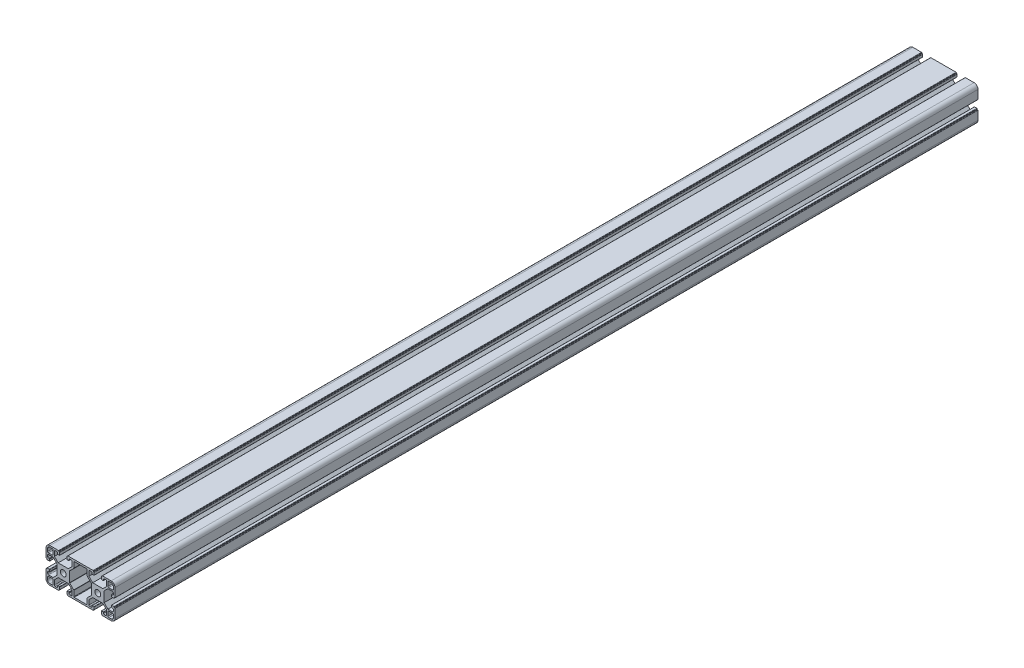
SolidWorks part; units mm, degrees
ref_plane "Front Plane" through (0, 0, 0) normal (0, 0, 1) x (1, 0, 0)
ref_plane "Top Plane" through (0, 0, 0) normal (0, 1, 0) x (1, 0, 0)
ref_plane "Right Plane" through (0, 0, 0) normal (1, 0, 0) x (0, 0, -1)
sketch "Model" plane through (0, 0, 0) normal (0, 0, 1) x (1, 0, 0)
  line L0 (3124.8642, 1448.2024) -> (3124.8642, 1456.7024) construction
  line L1 (3120.6142, 1452.4524) -> (3129.1142, 1452.4524) construction
  line L2 (3180.3642, 1470.6524) -> (3177.6142, 1470.6524)
  line L3 (3183.0642, 1465.2024) -> (3183.0642, 1467.9524)
  line L4 (3176.6142, 1469.6524) -> (3176.6142, 1465.2024)
  line L5 (3177.6142, 1464.2024) -> (3182.0642, 1464.2024)
  line L6 (3183.0642, 1436.9524) -> (3183.0642, 1439.7024)
  line L7 (3177.6142, 1434.2524) -> (3180.3642, 1434.2524)
  line L8 (3182.0642, 1440.7024) -> (3177.6142, 1440.7024)
  line L9 (3176.6142, 1439.7024) -> (3176.6142, 1435.2524)
  line L10 (3106.6642, 1465.2024) -> (3106.6642, 1467.9524)
  line L11 (3109.3642, 1470.6524) -> (3112.1142, 1470.6524)
  line L12 (3112.1142, 1464.2024) -> (3107.6642, 1464.2024)
  line L13 (3113.1142, 1469.6524) -> (3113.1142, 1465.2024)
  line L14 (3152.6142, 1434.9524) -> (3152.6142, 1441.3388)
  line L15 (3137.1142, 1441.3388) -> (3137.1142, 1434.9524)
  line L16 (3152.7606, 1441.6923) -> (3157.3177, 1446.2494)
  line L17 (3132.4106, 1446.2494) -> (3136.9677, 1441.6923)
  line L18 (3157.4642, 1446.603) -> (3157.4642, 1458.3018)
  line L19 (3132.2642, 1458.3018) -> (3132.2642, 1446.603)
  line L20 (3157.3177, 1458.6553) -> (3152.7606, 1463.2124)
  line L21 (3136.9677, 1463.2124) -> (3132.4106, 1458.6553)
  line L22 (3152.6142, 1463.566) -> (3152.6142, 1469.9524)
  line L23 (3137.1142, 1469.9524) -> (3137.1142, 1463.566)
  line L24 (3112.1142, 1434.2524) -> (3109.3642, 1434.2524)
  line L25 (3106.6642, 1436.9524) -> (3106.6642, 1439.7024)
  line L26 (3113.1142, 1439.7024) -> (3113.1142, 1435.2524)
  line L27 (3107.6642, 1440.7024) -> (3112.1142, 1440.7024)
  line L28 (3107.8642, 1445.8524) -> (3108.8642, 1445.8524)
  line L29 (3106.8642, 1443.2024) -> (3106.8642, 1444.8524)
  line L30 (3109.1642, 1446.1524) -> (3109.1642, 1448.0524)
  line L31 (3113.1293, 1442.2024) -> (3107.8642, 1442.2024)
  line L32 (3117.4642, 1446.5373) -> (3113.1293, 1442.2024)
  line L33 (3108.8642, 1448.3524) -> (3106.1642, 1448.3524)
  line L34 (3117.4642, 1458.3674) -> (3117.4642, 1446.5373)
  line L35 (3113.1293, 1462.7024) -> (3117.4642, 1458.3674)
  line L36 (3105.8642, 1448.0524) -> (3105.8642, 1447.5524)
  line L37 (3107.8642, 1462.7024) -> (3113.1293, 1462.7024)
  line L38 (3105.6642, 1447.3524) -> (3105.1642, 1447.3524)
  line L39 (3106.8642, 1460.0524) -> (3106.8642, 1461.7024)
  line L40 (3104.8642, 1447.0524) -> (3104.8642, 1436.9524)
  line L41 (3108.8642, 1459.0524) -> (3107.8642, 1459.0524)
  line L42 (3109.3642, 1432.4524) -> (3119.4642, 1432.4524)
  line L43 (3109.1642, 1456.8524) -> (3109.1642, 1458.7524)
  line L44 (3119.7642, 1432.7524) -> (3119.7642, 1433.2524)
  line L45 (3106.1642, 1456.5524) -> (3108.8642, 1456.5524)
  line L46 (3119.9642, 1433.4524) -> (3120.4642, 1433.4524)
  line L47 (3105.8642, 1457.3524) -> (3105.8642, 1456.8524)
  line L48 (3120.7642, 1433.7524) -> (3120.7642, 1436.4524)
  line L49 (3105.1642, 1457.5524) -> (3105.6642, 1457.5524)
  line L50 (3120.4642, 1436.7524) -> (3118.5642, 1436.7524)
  line L51 (3104.8642, 1467.9524) -> (3104.8642, 1457.8524)
  line L52 (3118.2642, 1436.4524) -> (3118.2642, 1435.4524)
  line L53 (3119.4642, 1472.4524) -> (3109.3642, 1472.4524)
  line L54 (3117.2642, 1434.4524) -> (3115.6142, 1434.4524)
  line L55 (3119.7642, 1471.6524) -> (3119.7642, 1472.1524)
  line L56 (3114.6142, 1435.4524) -> (3114.6142, 1440.7174)
  line L57 (3120.4642, 1471.4524) -> (3119.9642, 1471.4524)
  line L58 (3114.6142, 1440.7174) -> (3118.9491, 1445.0524)
  line L59 (3118.9491, 1445.0524) -> (3130.7793, 1445.0524)
  line L60 (3120.7642, 1468.4524) -> (3120.7642, 1471.1524)
  line L61 (3130.7793, 1445.0524) -> (3135.1142, 1440.7174)
  line L62 (3135.1142, 1440.7174) -> (3135.1142, 1435.4524)
  line L63 (3118.5642, 1468.1524) -> (3120.4642, 1468.1524)
  line L64 (3134.1142, 1434.4524) -> (3132.4642, 1434.4524)
  line L65 (3118.2642, 1469.4524) -> (3118.2642, 1468.4524)
  line L66 (3131.4642, 1435.4524) -> (3131.4642, 1436.4524)
  line L67 (3115.6142, 1470.4524) -> (3117.2642, 1470.4524)
  line L68 (3131.1642, 1436.7524) -> (3129.2642, 1436.7524)
  line L69 (3114.6142, 1464.1873) -> (3114.6142, 1469.4524)
  line L70 (3118.9491, 1459.8524) -> (3114.6142, 1464.1873)
  line L71 (3128.9642, 1436.4524) -> (3128.9642, 1433.7524)
  line L72 (3130.7793, 1459.8524) -> (3118.9491, 1459.8524)
  line L73 (3135.1142, 1464.1873) -> (3130.7793, 1459.8524)
  line L74 (3129.2642, 1433.4524) -> (3129.7642, 1433.4524)
  line L75 (3135.1142, 1469.4524) -> (3135.1142, 1464.1873)
  line L76 (3129.9642, 1433.2524) -> (3129.9642, 1432.7524)
  line L77 (3132.4642, 1470.4524) -> (3134.1142, 1470.4524)
  line L78 (3131.4642, 1468.4524) -> (3131.4642, 1469.4524)
  line L79 (3129.2642, 1468.1524) -> (3131.1642, 1468.1524)
  line L80 (3159.7642, 1432.7524) -> (3159.7642, 1433.2524)
  line L81 (3128.9642, 1471.1524) -> (3128.9642, 1468.4524)
  line L82 (3159.9642, 1433.4524) -> (3160.4642, 1433.4524)
  line L83 (3129.7642, 1471.4524) -> (3129.2642, 1471.4524)
  line L84 (3160.7642, 1433.7524) -> (3160.7642, 1436.4524)
  line L85 (3129.9642, 1472.1524) -> (3129.9642, 1471.6524)
  line L86 (3160.4642, 1436.7524) -> (3158.5642, 1436.7524)
  line L87 (3158.2642, 1436.4524) -> (3158.2642, 1435.4524)
  line L88 (3157.2642, 1434.4524) -> (3155.6142, 1434.4524)
  line L89 (3159.7642, 1471.6524) -> (3159.7642, 1472.1524)
  line L90 (3154.6142, 1435.4524) -> (3154.6142, 1440.7174)
  line L91 (3160.4642, 1471.4524) -> (3159.9642, 1471.4524)
  line L92 (3154.6142, 1440.7174) -> (3158.9491, 1445.0524)
  line L93 (3158.9491, 1445.0524) -> (3170.7793, 1445.0524)
  line L94 (3160.7642, 1468.4524) -> (3160.7642, 1471.1524)
  line L95 (3170.7793, 1445.0524) -> (3175.1142, 1440.7174)
  line L96 (3175.1142, 1440.7174) -> (3175.1142, 1435.4524)
  line L97 (3158.5642, 1468.1524) -> (3160.4642, 1468.1524)
  line L98 (3174.1142, 1434.4524) -> (3172.4642, 1434.4524)
  line L99 (3158.2642, 1469.4524) -> (3158.2642, 1468.4524)
  line L100 (3171.4642, 1435.4524) -> (3171.4642, 1436.4524)
  line L101 (3155.6142, 1470.4524) -> (3157.2642, 1470.4524)
  line L102 (3171.1642, 1436.7524) -> (3169.2642, 1436.7524)
  line L103 (3154.6142, 1464.1873) -> (3154.6142, 1469.4524)
  line L104 (3158.9491, 1459.8524) -> (3154.6142, 1464.1873)
  line L105 (3168.9642, 1436.4524) -> (3168.9642, 1433.7524)
  line L106 (3170.7793, 1459.8524) -> (3158.9491, 1459.8524)
  line L107 (3175.1142, 1464.1873) -> (3170.7793, 1459.8524)
  line L108 (3169.2642, 1433.4524) -> (3169.7642, 1433.4524)
  line L109 (3175.1142, 1469.4524) -> (3175.1142, 1464.1873)
  line L110 (3169.9642, 1433.2524) -> (3169.9642, 1432.7524)
  line L111 (3172.4642, 1470.4524) -> (3174.1142, 1470.4524)
  line L112 (3170.2642, 1432.4524) -> (3180.3642, 1432.4524)
  line L113 (3171.4642, 1468.4524) -> (3171.4642, 1469.4524)
  line L114 (3184.8642, 1436.9524) -> (3184.8642, 1447.0524)
  line L115 (3169.2642, 1468.1524) -> (3171.1642, 1468.1524)
  line L116 (3184.5642, 1447.3524) -> (3184.0642, 1447.3524)
  line L117 (3168.9642, 1471.1524) -> (3168.9642, 1468.4524)
  line L118 (3183.8642, 1447.5524) -> (3183.8642, 1448.0524)
  line L119 (3169.7642, 1471.4524) -> (3169.2642, 1471.4524)
  line L120 (3183.5642, 1448.3524) -> (3180.8642, 1448.3524)
  line L121 (3169.9642, 1472.1524) -> (3169.9642, 1471.6524)
  line L122 (3180.5642, 1448.0524) -> (3180.5642, 1446.1524)
  line L123 (3180.3642, 1472.4524) -> (3170.2642, 1472.4524)
  line L124 (3180.8642, 1445.8524) -> (3181.8642, 1445.8524)
  line L125 (3184.8642, 1457.8524) -> (3184.8642, 1467.9524)
  line L126 (3182.8642, 1444.8524) -> (3182.8642, 1443.2024)
  line L127 (3184.0642, 1457.5524) -> (3184.5642, 1457.5524)
  line L128 (3181.8642, 1442.2024) -> (3176.5991, 1442.2024)
  line L129 (3183.8642, 1456.8524) -> (3183.8642, 1457.3524)
  line L130 (3176.5991, 1442.2024) -> (3172.2642, 1446.5373)
  line L131 (3172.2642, 1446.5373) -> (3172.2642, 1458.3674)
  line L132 (3180.8642, 1456.5524) -> (3183.5642, 1456.5524)
  line L133 (3172.2642, 1458.3674) -> (3176.5991, 1462.7024)
  line L134 (3176.5991, 1462.7024) -> (3181.8642, 1462.7024)
  line L135 (3180.5642, 1458.7524) -> (3180.5642, 1456.8524)
  line L136 (3182.8642, 1461.7024) -> (3182.8642, 1460.0524)
  line L137 (3181.8642, 1459.0524) -> (3180.8642, 1459.0524)
  line L138 (3164.8642, 1448.2024) -> (3164.8642, 1456.7024) construction
  line L139 (3160.6142, 1452.4524) -> (3169.1142, 1452.4524) construction
  line L140 (3130.2642, 1432.4524) -> (3159.4642, 1432.4524)
  line L141 (3152.1142, 1434.4524) -> (3137.6142, 1434.4524)
  line L142 (3130.2642, 1472.4524) -> (3159.4642, 1472.4524)
  line L143 (3152.1142, 1470.4524) -> (3137.6142, 1470.4524)
  circle A0 centre (3164.8642, 1452.4524) radius 3.4
  arc A1 (3183.0642, 1467.9524) -> (3180.3642, 1470.6524) centre (3180.3642, 1467.9524) ccw
  arc A2 (3177.6142, 1470.6524) -> (3176.6142, 1469.6524) centre (3177.6142, 1469.6524) ccw
  arc A3 (3182.0642, 1464.2024) -> (3183.0642, 1465.2024) centre (3182.0642, 1465.2024) ccw
  arc A4 (3176.6142, 1465.2024) -> (3177.6142, 1464.2024) centre (3177.6142, 1465.2024) ccw
  arc A5 (3180.3642, 1434.2524) -> (3183.0642, 1436.9524) centre (3180.3642, 1436.9524) ccw
  arc A6 (3183.0642, 1439.7024) -> (3182.0642, 1440.7024) centre (3182.0642, 1439.7024) ccw
  arc A7 (3176.6142, 1435.2524) -> (3177.6142, 1434.2524) centre (3177.6142, 1435.2524) ccw
  arc A8 (3177.6142, 1440.7024) -> (3176.6142, 1439.7024) centre (3177.6142, 1439.7024) ccw
  circle A9 centre (3124.8642, 1452.4524) radius 3.4
  arc A10 (3109.3642, 1470.6524) -> (3106.6642, 1467.9524) centre (3109.3642, 1467.9524) ccw
  arc A11 (3106.6642, 1465.2024) -> (3107.6642, 1464.2024) centre (3107.6642, 1465.2024) ccw
  arc A12 (3113.1142, 1469.6524) -> (3112.1142, 1470.6524) centre (3112.1142, 1469.6524) ccw
  arc A13 (3112.1142, 1464.2024) -> (3113.1142, 1465.2024) centre (3112.1142, 1465.2024) ccw
  arc A14 (3152.1142, 1434.4524) -> (3152.6142, 1434.9524) centre (3152.1142, 1434.9524) ccw
  arc A15 (3137.1142, 1434.9524) -> (3137.6142, 1434.4524) centre (3137.6142, 1434.9524) ccw
  arc A16 (3152.7606, 1441.6923) -> (3152.6142, 1441.3388) centre (3153.1142, 1441.3388) ccw
  arc A17 (3137.1142, 1441.3388) -> (3136.9677, 1441.6923) centre (3136.6142, 1441.3388) ccw
  arc A18 (3157.3177, 1446.2494) -> (3157.4642, 1446.603) centre (3156.9642, 1446.603) ccw
  arc A19 (3132.2642, 1446.603) -> (3132.4106, 1446.2494) centre (3132.7642, 1446.603) ccw
  arc A20 (3157.4642, 1458.3018) -> (3157.3177, 1458.6553) centre (3156.9642, 1458.3018) ccw
  arc A21 (3132.4106, 1458.6553) -> (3132.2642, 1458.3018) centre (3132.7642, 1458.3018) ccw
  arc A22 (3152.6142, 1463.566) -> (3152.7606, 1463.2124) centre (3153.1142, 1463.566) ccw
  arc A23 (3136.9677, 1463.2124) -> (3137.1142, 1463.566) centre (3136.6142, 1463.566) ccw
  arc A24 (3152.6142, 1469.9524) -> (3152.1142, 1470.4524) centre (3152.1142, 1469.9524) ccw
  arc A25 (3137.6142, 1470.4524) -> (3137.1142, 1469.9524) centre (3137.6142, 1469.9524) ccw
  arc A26 (3106.6642, 1436.9524) -> (3109.3642, 1434.2524) centre (3109.3642, 1436.9524) ccw
  arc A27 (3112.1142, 1434.2524) -> (3113.1142, 1435.2524) centre (3112.1142, 1435.2524) ccw
  arc A28 (3107.6642, 1440.7024) -> (3106.6642, 1439.7024) centre (3107.6642, 1439.7024) ccw
  arc A29 (3113.1142, 1439.7024) -> (3112.1142, 1440.7024) centre (3112.1142, 1439.7024) ccw
  arc A30 (3107.8642, 1445.8524) -> (3106.8642, 1444.8524) centre (3107.8642, 1444.8524) ccw
  arc A31 (3108.8642, 1445.8524) -> (3109.1642, 1446.1524) centre (3108.8642, 1446.1524) ccw
  arc A32 (3106.8642, 1443.2024) -> (3107.8642, 1442.2024) centre (3107.8642, 1443.2024) ccw
  arc A33 (3109.1642, 1448.0524) -> (3108.8642, 1448.3524) centre (3108.8642, 1448.0524) ccw
  arc A34 (3106.1642, 1448.3524) -> (3105.8642, 1448.0524) centre (3106.1642, 1448.0524) ccw
  arc A35 (3105.6642, 1447.3524) -> (3105.8642, 1447.5524) centre (3105.6642, 1447.5524) ccw
  arc A36 (3107.8642, 1462.7024) -> (3106.8642, 1461.7024) centre (3107.8642, 1461.7024) ccw
  arc A37 (3105.1642, 1447.3524) -> (3104.8642, 1447.0524) centre (3105.1642, 1447.0524) ccw
  arc A38 (3106.8642, 1460.0524) -> (3107.8642, 1459.0524) centre (3107.8642, 1460.0524) ccw
  arc A39 (3104.8642, 1436.9524) -> (3109.3642, 1432.4524) centre (3109.3642, 1436.9524) ccw
  arc A40 (3109.1642, 1458.7524) -> (3108.8642, 1459.0524) centre (3108.8642, 1458.7524) ccw
  arc A41 (3119.4642, 1432.4524) -> (3119.7642, 1432.7524) centre (3119.4642, 1432.7524) ccw
  arc A42 (3108.8642, 1456.5524) -> (3109.1642, 1456.8524) centre (3108.8642, 1456.8524) ccw
  arc A43 (3119.9642, 1433.4524) -> (3119.7642, 1433.2524) centre (3119.9642, 1433.2524) ccw
  arc A44 (3105.8642, 1456.8524) -> (3106.1642, 1456.5524) centre (3106.1642, 1456.8524) ccw
  arc A45 (3120.4642, 1433.4524) -> (3120.7642, 1433.7524) centre (3120.4642, 1433.7524) ccw
  arc A46 (3105.8642, 1457.3524) -> (3105.6642, 1457.5524) centre (3105.6642, 1457.3524) ccw
  arc A47 (3120.7642, 1436.4524) -> (3120.4642, 1436.7524) centre (3120.4642, 1436.4524) ccw
  arc A48 (3104.8642, 1457.8524) -> (3105.1642, 1457.5524) centre (3105.1642, 1457.8524) ccw
  arc A49 (3118.5642, 1436.7524) -> (3118.2642, 1436.4524) centre (3118.5642, 1436.4524) ccw
  arc A50 (3109.3642, 1472.4524) -> (3104.8642, 1467.9524) centre (3109.3642, 1467.9524) ccw
  arc A51 (3117.2642, 1434.4524) -> (3118.2642, 1435.4524) centre (3117.2642, 1435.4524) ccw
  arc A52 (3119.7642, 1472.1524) -> (3119.4642, 1472.4524) centre (3119.4642, 1472.1524) ccw
  arc A53 (3114.6142, 1435.4524) -> (3115.6142, 1434.4524) centre (3115.6142, 1435.4524) ccw
  arc A54 (3119.7642, 1471.6524) -> (3119.9642, 1471.4524) centre (3119.9642, 1471.6524) ccw
  arc A55 (3120.7642, 1471.1524) -> (3120.4642, 1471.4524) centre (3120.4642, 1471.1524) ccw
  arc A56 (3120.4642, 1468.1524) -> (3120.7642, 1468.4524) centre (3120.4642, 1468.4524) ccw
  arc A57 (3134.1142, 1434.4524) -> (3135.1142, 1435.4524) centre (3134.1142, 1435.4524) ccw
  arc A58 (3118.2642, 1468.4524) -> (3118.5642, 1468.1524) centre (3118.5642, 1468.4524) ccw
  arc A59 (3131.4642, 1435.4524) -> (3132.4642, 1434.4524) centre (3132.4642, 1435.4524) ccw
  arc A60 (3118.2642, 1469.4524) -> (3117.2642, 1470.4524) centre (3117.2642, 1469.4524) ccw
  arc A61 (3131.4642, 1436.4524) -> (3131.1642, 1436.7524) centre (3131.1642, 1436.4524) ccw
  arc A62 (3115.6142, 1470.4524) -> (3114.6142, 1469.4524) centre (3115.6142, 1469.4524) ccw
  arc A63 (3129.2642, 1436.7524) -> (3128.9642, 1436.4524) centre (3129.2642, 1436.4524) ccw
  arc A64 (3128.9642, 1433.7524) -> (3129.2642, 1433.4524) centre (3129.2642, 1433.7524) ccw
  arc A65 (3129.9642, 1433.2524) -> (3129.7642, 1433.4524) centre (3129.7642, 1433.2524) ccw
  arc A66 (3135.1142, 1469.4524) -> (3134.1142, 1470.4524) centre (3134.1142, 1469.4524) ccw
  arc A67 (3129.9642, 1432.7524) -> (3130.2642, 1432.4524) centre (3130.2642, 1432.7524) ccw
  arc A68 (3132.4642, 1470.4524) -> (3131.4642, 1469.4524) centre (3132.4642, 1469.4524) ccw
  arc A69 (3131.1642, 1468.1524) -> (3131.4642, 1468.4524) centre (3131.1642, 1468.4524) ccw
  arc A70 (3159.4642, 1432.4524) -> (3159.7642, 1432.7524) centre (3159.4642, 1432.7524) ccw
  arc A71 (3128.9642, 1468.4524) -> (3129.2642, 1468.1524) centre (3129.2642, 1468.4524) ccw
  arc A72 (3159.9642, 1433.4524) -> (3159.7642, 1433.2524) centre (3159.9642, 1433.2524) ccw
  arc A73 (3129.2642, 1471.4524) -> (3128.9642, 1471.1524) centre (3129.2642, 1471.1524) ccw
  arc A74 (3160.4642, 1433.4524) -> (3160.7642, 1433.7524) centre (3160.4642, 1433.7524) ccw
  arc A75 (3129.7642, 1471.4524) -> (3129.9642, 1471.6524) centre (3129.7642, 1471.6524) ccw
  arc A76 (3160.7642, 1436.4524) -> (3160.4642, 1436.7524) centre (3160.4642, 1436.4524) ccw
  arc A77 (3130.2642, 1472.4524) -> (3129.9642, 1472.1524) centre (3130.2642, 1472.1524) ccw
  arc A78 (3158.5642, 1436.7524) -> (3158.2642, 1436.4524) centre (3158.5642, 1436.4524) ccw
  arc A79 (3157.2642, 1434.4524) -> (3158.2642, 1435.4524) centre (3157.2642, 1435.4524) ccw
  arc A80 (3159.7642, 1472.1524) -> (3159.4642, 1472.4524) centre (3159.4642, 1472.1524) ccw
  arc A81 (3154.6142, 1435.4524) -> (3155.6142, 1434.4524) centre (3155.6142, 1435.4524) ccw
  arc A82 (3159.7642, 1471.6524) -> (3159.9642, 1471.4524) centre (3159.9642, 1471.6524) ccw
  arc A83 (3160.7642, 1471.1524) -> (3160.4642, 1471.4524) centre (3160.4642, 1471.1524) ccw
  arc A84 (3160.4642, 1468.1524) -> (3160.7642, 1468.4524) centre (3160.4642, 1468.4524) ccw
  arc A85 (3174.1142, 1434.4524) -> (3175.1142, 1435.4524) centre (3174.1142, 1435.4524) ccw
  arc A86 (3158.2642, 1468.4524) -> (3158.5642, 1468.1524) centre (3158.5642, 1468.4524) ccw
  arc A87 (3171.4642, 1435.4524) -> (3172.4642, 1434.4524) centre (3172.4642, 1435.4524) ccw
  arc A88 (3158.2642, 1469.4524) -> (3157.2642, 1470.4524) centre (3157.2642, 1469.4524) ccw
  arc A89 (3171.4642, 1436.4524) -> (3171.1642, 1436.7524) centre (3171.1642, 1436.4524) ccw
  arc A90 (3155.6142, 1470.4524) -> (3154.6142, 1469.4524) centre (3155.6142, 1469.4524) ccw
  arc A91 (3169.2642, 1436.7524) -> (3168.9642, 1436.4524) centre (3169.2642, 1436.4524) ccw
  arc A92 (3168.9642, 1433.7524) -> (3169.2642, 1433.4524) centre (3169.2642, 1433.7524) ccw
  arc A93 (3169.9642, 1433.2524) -> (3169.7642, 1433.4524) centre (3169.7642, 1433.2524) ccw
  arc A94 (3175.1142, 1469.4524) -> (3174.1142, 1470.4524) centre (3174.1142, 1469.4524) ccw
  arc A95 (3169.9642, 1432.7524) -> (3170.2642, 1432.4524) centre (3170.2642, 1432.7524) ccw
  arc A96 (3172.4642, 1470.4524) -> (3171.4642, 1469.4524) centre (3172.4642, 1469.4524) ccw
  arc A97 (3180.3642, 1432.4524) -> (3184.8642, 1436.9524) centre (3180.3642, 1436.9524) ccw
  arc A98 (3171.1642, 1468.1524) -> (3171.4642, 1468.4524) centre (3171.1642, 1468.4524) ccw
  arc A99 (3184.8642, 1447.0524) -> (3184.5642, 1447.3524) centre (3184.5642, 1447.0524) ccw
  arc A100 (3168.9642, 1468.4524) -> (3169.2642, 1468.1524) centre (3169.2642, 1468.4524) ccw
  arc A101 (3183.8642, 1447.5524) -> (3184.0642, 1447.3524) centre (3184.0642, 1447.5524) ccw
  arc A102 (3169.2642, 1471.4524) -> (3168.9642, 1471.1524) centre (3169.2642, 1471.1524) ccw
  arc A103 (3183.8642, 1448.0524) -> (3183.5642, 1448.3524) centre (3183.5642, 1448.0524) ccw
  arc A104 (3169.7642, 1471.4524) -> (3169.9642, 1471.6524) centre (3169.7642, 1471.6524) ccw
  arc A105 (3180.8642, 1448.3524) -> (3180.5642, 1448.0524) centre (3180.8642, 1448.0524) ccw
  arc A106 (3170.2642, 1472.4524) -> (3169.9642, 1472.1524) centre (3170.2642, 1472.1524) ccw
  arc A107 (3180.5642, 1446.1524) -> (3180.8642, 1445.8524) centre (3180.8642, 1446.1524) ccw
  arc A108 (3184.8642, 1467.9524) -> (3180.3642, 1472.4524) centre (3180.3642, 1467.9524) ccw
  arc A109 (3182.8642, 1444.8524) -> (3181.8642, 1445.8524) centre (3181.8642, 1444.8524) ccw
  arc A110 (3184.5642, 1457.5524) -> (3184.8642, 1457.8524) centre (3184.5642, 1457.8524) ccw
  arc A111 (3181.8642, 1442.2024) -> (3182.8642, 1443.2024) centre (3181.8642, 1443.2024) ccw
  arc A112 (3184.0642, 1457.5524) -> (3183.8642, 1457.3524) centre (3184.0642, 1457.3524) ccw
  arc A113 (3183.5642, 1456.5524) -> (3183.8642, 1456.8524) centre (3183.5642, 1456.8524) ccw
  arc A114 (3180.5642, 1456.8524) -> (3180.8642, 1456.5524) centre (3180.8642, 1456.8524) ccw
  arc A115 (3182.8642, 1461.7024) -> (3181.8642, 1462.7024) centre (3181.8642, 1461.7024) ccw
  arc A116 (3180.8642, 1459.0524) -> (3180.5642, 1458.7524) centre (3180.8642, 1458.7524) ccw
  arc A117 (3181.8642, 1459.0524) -> (3182.8642, 1460.0524) centre (3181.8642, 1460.0524) ccw
extrude "Boss-Extrude1" add sketch "Model" along normal blind 1000
